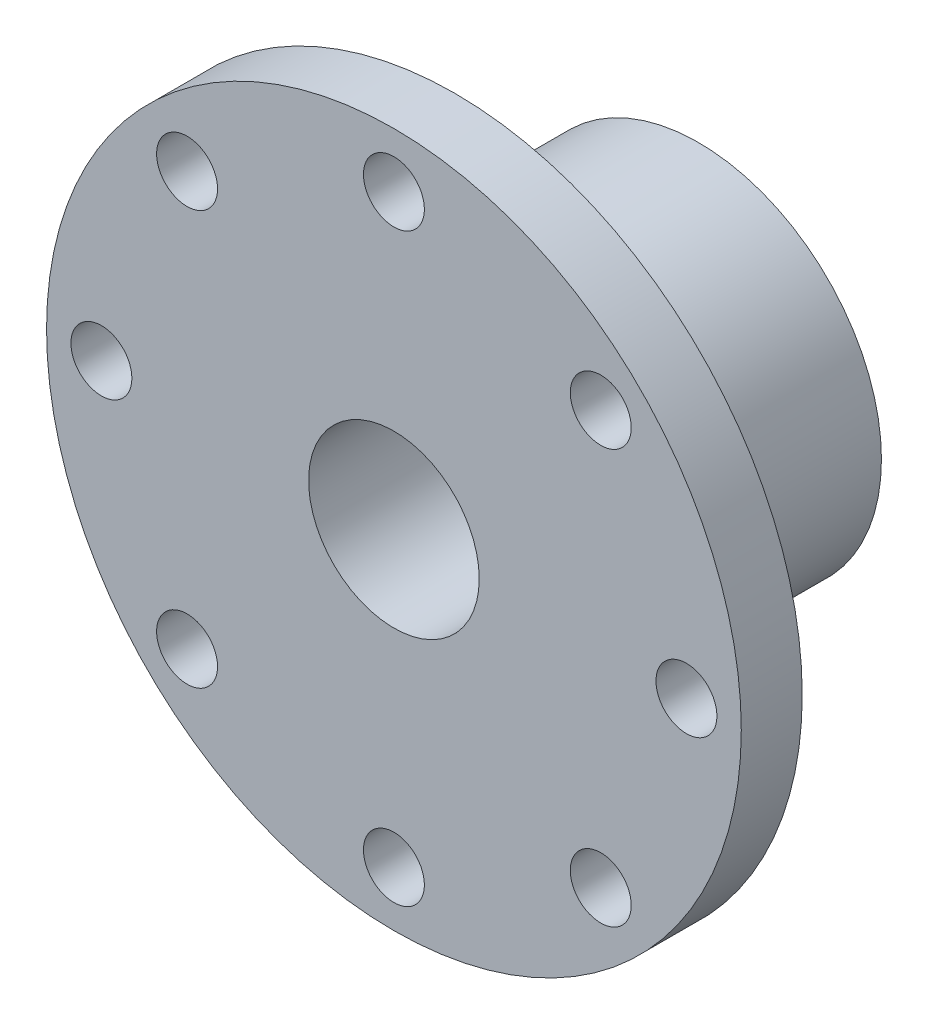
SolidWorks part; units mm, degrees
ref_plane "前视基准面" through (0, 0, 0) normal (0, 0, 1) x (1, 0, 0)
ref_plane "上视基准面" through (0, 0, 0) normal (0, 1, 0) x (1, 0, 0)
ref_plane "右视基准面" through (0, 0, 0) normal (1, 0, 0) x (0, 0, -1)
sketch "草图1" plane through (0, 0, 0) normal (0, 0, 1) x (1, 0, 0)
  circle A0 centre (0, 0) radius 15
  circle A1 centre (0, 0) radius 7
  dimension "D1" = 14
  dimension "D2" = 30
extrude "凸台-拉伸1" add sketch "草图1" along normal blind 20 contours A0
sketch "草图2" plane through (0, 0, 20) normal (0, 0, 1) x (1, 0, 0)
  circle A0 centre (0, 0) radius 7
  circle A1 centre (0, 0) radius 28.5
  dimension "D1" = 57
extrude "凸台-拉伸2" add sketch "草图2" along normal blind 5
sketch "草图3" plane through (0, 0, 25) normal (0, 0, 1) x (1, 0, 0)
  circle A0 centre (0, 0) radius 24 construction
  circle A1 centre (0, -24) radius 2.5
  circle A2 centre (-16.9706, -16.9706) radius 2.5
  circle A3 centre (-24, 0) radius 2.5
  circle A4 centre (-16.9706, 16.9706) radius 2.5
  circle A5 centre (0, 24) radius 2.5
  circle A6 centre (16.9706, 16.9706) radius 2.5
  circle A7 centre (24, 0) radius 2.5
  circle A8 centre (16.9706, -16.9706) radius 2.5
  dimension "D1" = 48
  dimension "D2" = 8
extrude "切除-拉伸1" cut sketch "草图3" against normal blind 5
sketch "草图4" plane through (0, 0, 0) normal (0, 1, 0) x (1, 0, 0)
  line L0 (0, 0) -> (0, -10) construction
  circle A0 centre (0, -10) radius 3
extrude "切除-拉伸2" cut sketch "草图4" against normal blind 20
